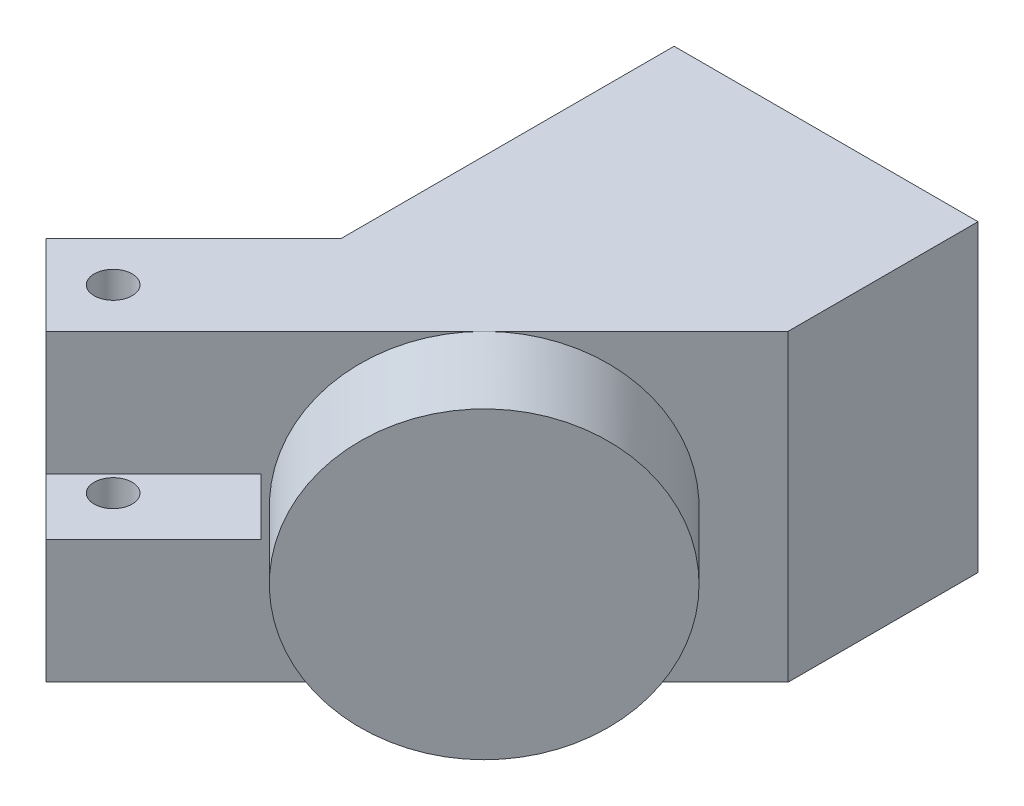
SolidWorks part; units mm, degrees
ref_plane "前视基准面" through (0, 0, 0) normal (0, 0, 1) x (1, 0, 0)
ref_plane "上视基准面" through (0, 0, 0) normal (0, 1, 0) x (1, 0, 0)
ref_plane "右视基准面" through (0, 0, 0) normal (1, 0, 0) x (0, 0, -1)
sketch "草图1" plane through (0, 0, 0) normal (0, 0, 1) x (1, 0, 0)
  line L1 (0, 0) -> (16, 0)
  line L2 (0, 0) -> (0, 16)
  line L3 (0, 16) -> (16, 16)
  line L4 (16, 0) -> (16, 16)
  line L5 (3, 3) -> (13, 3)
  line L6 (3, 3) -> (3, 13)
  line L7 (3, 13) -> (13, 13)
  line L8 (13, 3) -> (13, 13)
  point P5 (3, 3)
extrude "凸台-拉伸1" add sketch "草图1" along normal blind 10
sketch "草图2" plane through (0, 0, 0) normal (0, -1, 0) x (1, 0, 0)
  line L0 (0, 10) -> (0, 26)
  line L1 (0, 26) -> (16, 10)
  line L2 (16, 10) -> (0, 10)
sketch "草图5" plane through (0, 0, 0) normal (0, 0, -1) x (-1, 0, 0)
  line L1 (-3, 3) -> (-13, 3)
  line L2 (-3, 3) -> (-3, 13)
  line L3 (-3, 13) -> (-13, 13)
  line L4 (-13, 3) -> (-13, 13)
extrude "凸台-拉伸2" add sketch "草图2" against normal blind 16
sketch "草图6" plane through (13, 0, 13) normal (0.7071, 0, 0.7071) x (0.7071, 0, -0.7071)
  line L0 (-7.0711, 0) -> (-7.0711, 16)
  line L1 (4.2426, 0) -> (-18.3848, 0) construction
  line L2 (4.2426, 16) -> (-18.3848, 16) construction
  circle A0 centre (-7.0711, 8) radius 8
  point P8 (0, 0)
extrude "凸台-拉伸3" add sketch "草图6" along normal blind 5 contours L0 A0 | L0 A0
sketch "草图10" plane through (0, 16, 0) normal (0, 1, 0) x (1, 0, 0)
  line L0 (0, -26) -> (-3.5355, -29.5355)
  line L1 (-3.5355, -29.5355) -> (-7.7782, -25.2929)
  line L2 (-7.7782, -25.2929) -> (0, -17.5147)
  line L3 (0, -26) -> (0, 0) construction
  line L4 (0, -17.5147) -> (0, -26)
  point P7 (0, 0)
  point P8 (0, 0)
extrude "凸台-拉伸5" add sketch "草图10" against normal blind 16
sketch "草图12" plane through (-16.5355, 0, 16.5355) normal (-0.7071, 0, 0.7071) x (0.7071, 0, 0.7071)
  line L0 (18.3848, 0) -> (18.3848, 16) construction
  line L1 (12.3848, 0) -> (12.3848, 16) construction
  line L2 (18.3848, 9.5) -> (12.3848, 9.5)
  line L3 (18.3848, 9.5) -> (18.3848, 6.5)
  line L4 (18.3848, 6.5) -> (12.3848, 6.5)
  line L5 (12.3848, 9.5) -> (12.3848, 6.5)
  point P0 (18.3848, 9.5)
  point P1 (18.3848, 5)
  point P10 (0, 0)
  point P11 (0, 0)
  point P12 (0, 0)
  point P13 (0, 0)
  point P14 (0, 0)
  point P15 (0, 0)
extrude "切除-拉伸2" cut sketch "草图12" against normal blind 8
sketch "草图13" plane through (0, 16, 0) normal (0, 1, 0) x (1, 0, 0)
  line L0 (-3.5355, -29.5355) -> (-1.7678, -27.7678)
  line L1 (8, -18) -> (-3.5355, -29.5355) construction
  line L2 (-1.7678, -27.7678) -> (-6.0104, -23.5251)
  line L3 (0, -17.5147) -> (-7.7782, -25.2929) construction
  circle A0 centre (-3.8891, -25.6464) radius 1
  point P10 (0, 0)
  point P11 (0, 0)
  point P12 (0, 0)
  point P13 (0, 0)
sketch "草图14" plane through (0, 16, 0) normal (0, 1, 0) x (1, 0, 0)
  point P0 (-2.1031, -27.4083)
extrude "切除-拉伸3" cut sketch "草图13" against normal blind 16 contours L2 A0 | L2 A0
